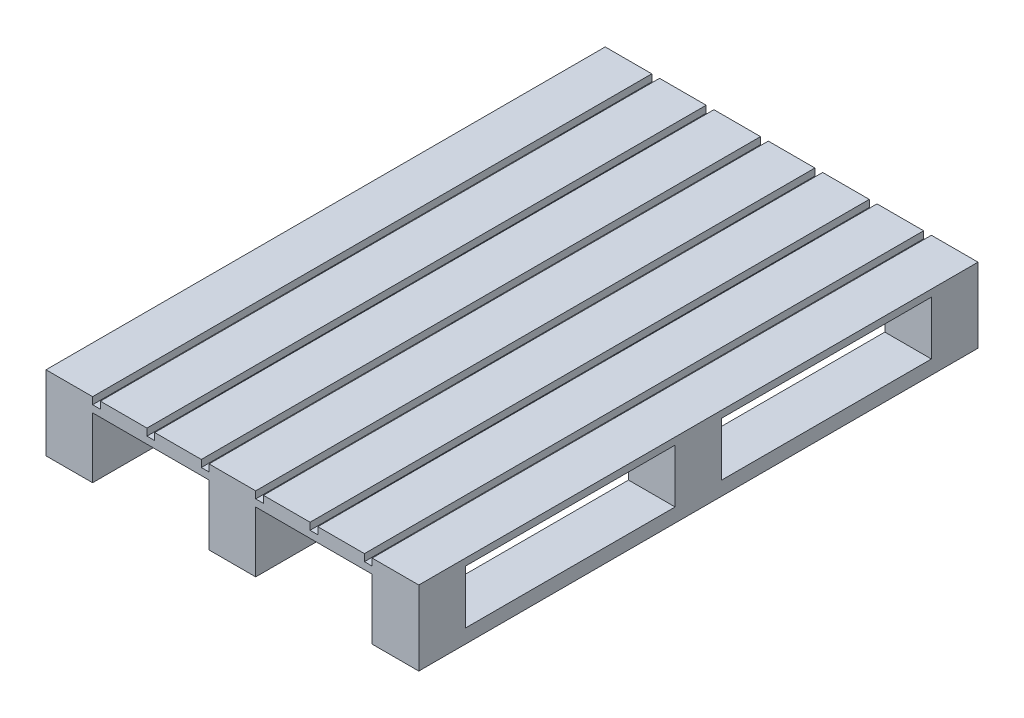
SolidWorks part; units mm, degrees
ref_plane "Front Plane" through (0, 0, 0) normal (0, 0, 1) x (1, 0, 0)
ref_plane "Top Plane" through (0, 0, 0) normal (0, 1, 0) x (1, 0, 0)
ref_plane "Right Plane" through (0, 0, 0) normal (1, 0, 0) x (0, 0, -1)
sketch "Sketch1" plane through (0, 0, 0) normal (0, 1, 0) x (1, 0, 0)
  line L1 (0, 0) -> (800, 0)
  line L2 (0, 0) -> (0, 1200)
  line L3 (0, 1200) -> (800, 1200)
  line L4 (800, 0) -> (800, 1200)
  dimension "D1" = 800
  dimension "D2" = 1200
extrude "Boss-Extrude1" add sketch "Sketch1" along normal blind 160
sketch "Sketch2" plane through (0, 0, 0) normal (0, 0, 1) x (1, 0, 0)
  line L0 (0, 0) -> (800, 0) construction
  line L1 (100, 0) -> (350, 0)
  line L2 (100, 0) -> (100, 130)
  line L3 (100, 130) -> (350, 130)
  line L4 (350, 0) -> (350, 130)
  line L5 (800, 160) -> (800, 0) construction
  line L6 (450, 0) -> (700, 0)
  line L7 (450, 0) -> (450, 130)
  line L8 (450, 130) -> (700, 130)
  line L9 (700, 0) -> (700, 130)
  line L10 (0, 160) -> (0, 0) construction
  line L11 (0, 160) -> (800, 160) construction
  dimension "D1" = 100
  dimension "D2" = 100
  dimension "D3" = 100
  dimension "D4" = 30
extrude "Cut-Extrude1" cut sketch "Sketch2" against normal through all
sketch "Sketch3" plane through (0, 0, 0) normal (-1, 0, 0) x (0, 0, 1)
  line L0 (-1200, 160) -> (-1200, 0) construction
  line L1 (-1100, 145) -> (-650, 145)
  line L2 (-1100, 145) -> (-1100, 30)
  line L3 (-1100, 30) -> (-650, 30)
  line L4 (-650, 145) -> (-650, 30)
  line L5 (-550, 145) -> (-100, 145)
  line L6 (-550, 145) -> (-550, 30)
  line L7 (-550, 30) -> (-100, 30)
  line L8 (-100, 145) -> (-100, 30)
  line L9 (0, 160) -> (0, 0) construction
  line L10 (-1200, 160) -> (0, 160) construction
  line L11 (-1200, 0) -> (0, 0) construction
  dimension "D1" = 100
  dimension "D2" = 100
  dimension "D3" = 100
  dimension "D4" = 15
  dimension "D5" = 30
extrude "Cut-Extrude2" cut sketch "Sketch3" against normal through all
sketch "Sketch4" plane through (0, 0, 0) normal (0, 0, 1) x (1, 0, 0)
  line L0 (0, 160) -> (800, 160) construction
  line L1 (100, 160) -> (116.6667, 160)
  line L2 (100, 160) -> (100, 145)
  line L3 (100, 145) -> (116.6667, 145)
  line L4 (116.6667, 160) -> (116.6667, 145)
  line L5 (0, 160) -> (0, 0) construction
  line L6 (216.6667, 160) -> (233.3333, 160)
  line L7 (216.6667, 160) -> (216.6667, 145)
  line L8 (216.6667, 145) -> (233.3333, 145)
  line L9 (233.3333, 160) -> (233.3333, 145)
  line L10 (350, 0) -> (350, 130) construction
  line L11 (333.3333, 160) -> (350, 160)
  line L12 (333.3333, 160) -> (333.3333, 145)
  line L13 (333.3333, 145) -> (350, 145)
  line L14 (350, 160) -> (350, 145)
  line L16 (400, -36.9537) -> (400, 215.914) construction
  line L17 (450, 160) -> (450, 145)
  line L18 (466.6667, 145) -> (450, 145)
  line L19 (466.6667, 160) -> (466.6667, 145)
  line L20 (466.6667, 160) -> (450, 160)
  line L21 (566.6667, 160) -> (566.6667, 145)
  line L22 (583.3333, 145) -> (566.6667, 145)
  line L23 (583.3333, 160) -> (583.3333, 145)
  line L24 (583.3333, 160) -> (566.6667, 160)
  line L25 (683.3333, 160) -> (683.3333, 145)
  line L26 (700, 145) -> (683.3333, 145)
  line L27 (700, 160) -> (700, 145)
  line L28 (700, 160) -> (683.3333, 160)
  dimension "D1" = 100
  dimension "D2" = 100
  dimension "D3" = 100
  dimension "D4" = 15
extrude "Cut-Extrude3" cut sketch "Sketch4" against normal through all
